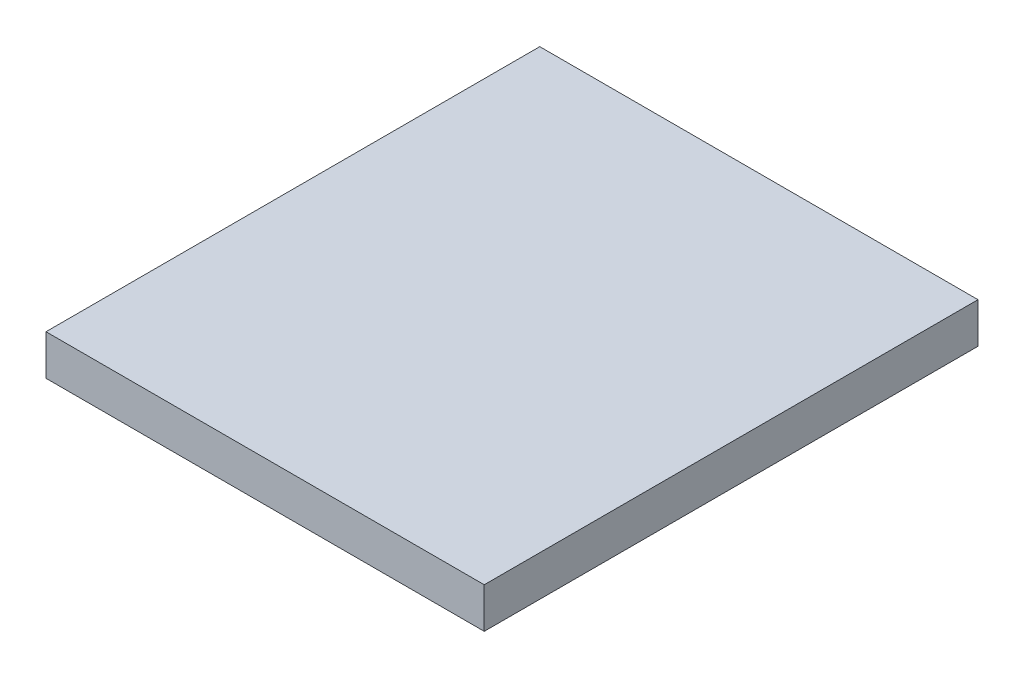
SolidWorks part; units mm, degrees
material "Glass"
ref_plane "Front Plane" through (0, 0, 0) normal (0, 0, 1) x (1, 0, 0)
ref_plane "Top Plane" through (0, 0, 0) normal (0, 1, 0) x (1, 0, 0)
ref_plane "Right Plane" through (0, 0, 0) normal (1, 0, 0) x (0, 0, -1)
sketch "Sketch1" plane through (0, 0, 0) normal (0, 0, 1) x (1, 0, 0)
  line L1 (0, 0) -> (22.5441, 0)
  line L2 (0, 0) -> (0, -2.0764)
  line L3 (0, -2.0764) -> (22.5441, -2.0764)
  line L4 (22.5441, 0) -> (22.5441, -2.0764)
extrude "Extrude1" add sketch "Sketch1" along normal blind 25.4
